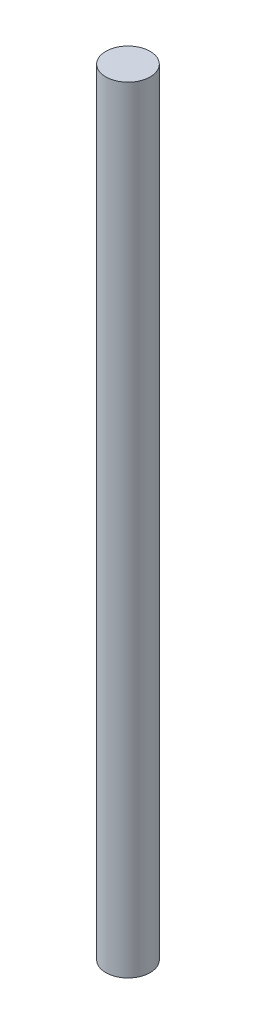
SolidWorks part; units mm, degrees
ref_plane "Alzado" through (0, 0, 0) normal (0, 0, 1) x (1, 0, 0)
ref_plane "Planta" through (0, 0, 0) normal (0, 1, 0) x (1, 0, 0)
ref_plane "Vista lateral" through (0, 0, 0) normal (1, 0, 0) x (0, 0, -1)
sketch "Croquis1" plane through (0, 0, 0) normal (0, 1, 0) x (1, 0, 0)
  circle A0 centre (0, 0) radius 4
  dimension "D1" = 8
extrude "Saliente-Extruir1" add sketch "Croquis1" along normal blind 140
